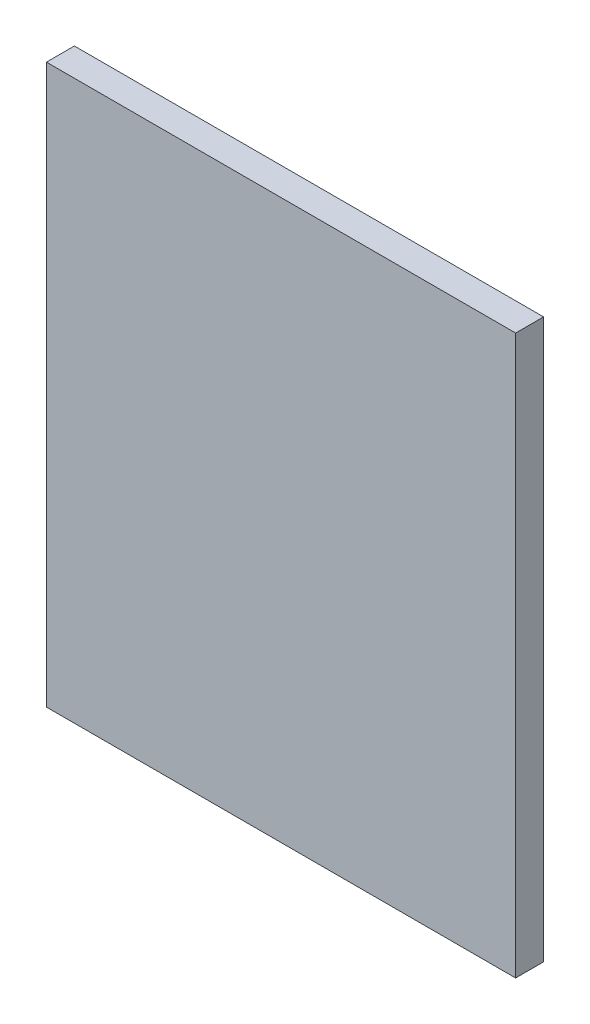
SolidWorks part; units mm, degrees
ref_plane "Plano frontal" through (0, 0, 0) normal (0, 0, 1) x (1, 0, 0)
ref_plane "Plano superior" through (0, 0, 0) normal (0, 1, 0) x (1, 0, 0)
ref_plane "Plano direito" through (0, 0, 0) normal (1, 0, 0) x (0, 0, -1)
sketch "Esboço1" plane through (0, 0, 0) normal (0, 0, 1) x (1, 0, 0)
  line L1 (-24.2012, 19.9116) -> (17.7988, 19.9116)
  line L2 (-24.2012, 19.9116) -> (-24.2012, -30.0884)
  line L3 (-24.2012, -30.0884) -> (17.7988, -30.0884)
  line L4 (17.7988, 19.9116) -> (17.7988, -30.0884)
  dimension "D1" = 42
  dimension "D2" = 50
extrude "Ressalto-extrusão1" add sketch "Esboço1" along normal blind 2.5
sketch "Esboço2" plane through (0, 0, 2.5) normal (0, 0, 1) x (1, 0, 0)
  line L0 (-3.2012, 19.9116) -> (-3.2012, -30.0884) construction
  line L1 (17.7988, 19.9116) -> (-24.2012, 19.9116) construction
  line L2 (-24.2012, -30.0884) -> (17.7988, -30.0884) construction
  line L3 (-16.7012, 19.9116) -> (-16.7012, -30.0884) construction
  line L4 (10.2988, 19.9116) -> (10.2988, -30.0884) construction
  dimension "D1" = 27
